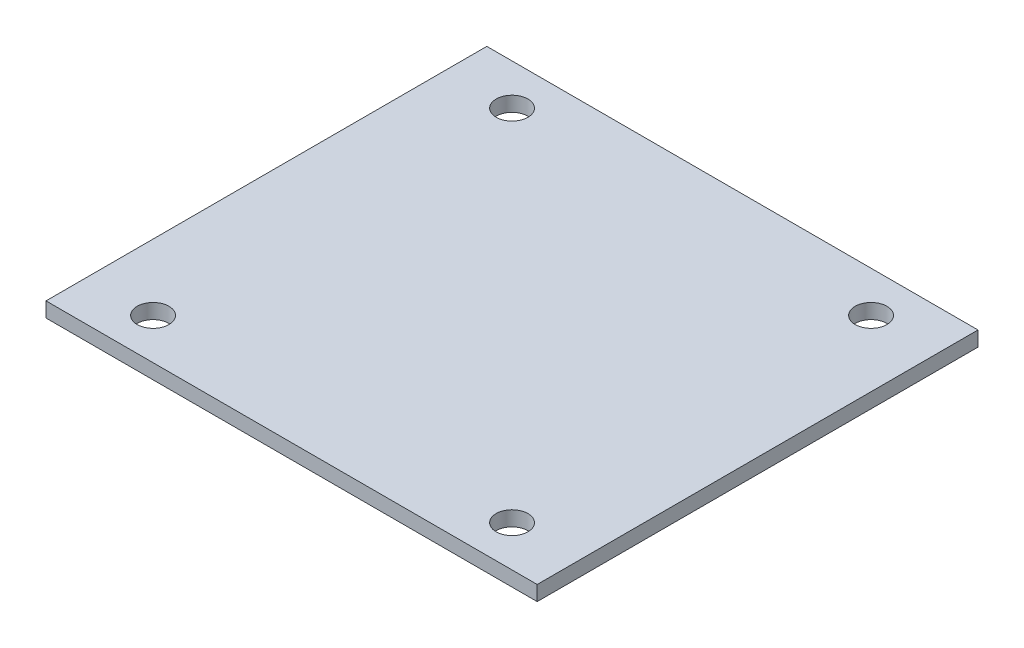
SolidWorks part; units mm, degrees
ref_plane "Front Plane" through (0, 0, 0) normal (0, 0, 1) x (1, 0, 0)
ref_plane "Top Plane" through (0, 0, 0) normal (0, 1, 0) x (1, 0, 0)
ref_plane "Right Plane" through (0, 0, 0) normal (1, 0, 0) x (0, 0, -1)
sketch "Sketch1" plane through (0, 0, 0) normal (0, 1, 0) x (1, 0, 0)
  line L0 (6.6675, 4.1275) -> (6.6675, 40.3275) construction
  line L1 (0, 44.45) -> (49.53, 44.45)
  line L2 (0, 44.45) -> (0, 0)
  line L3 (0, 0) -> (49.53, 0)
  line L4 (49.53, 44.45) -> (49.53, 0)
  line L5 (6.6675, 40.3275) -> (42.8675, 40.3275) construction
  line L6 (42.8675, 40.3275) -> (42.8675, 4.1275) construction
  line L7 (42.8675, 4.1275) -> (6.6675, 4.1275) construction
  circle A0 centre (6.6675, 4.1275) radius 1.6
  circle A1 centre (42.8675, 4.1275) radius 1.6
  circle A2 centre (42.8675, 40.3275) radius 1.6
  circle A3 centre (6.6675, 40.3275) radius 1.6
  dimension "D7" = 3.2
  dimension "D1" = 44.45
  dimension "D2" = 49.53
  dimension "D3" = 4.1275
  dimension "D4" = 6.6675
  dimension "D5" = 36.2
  dimension "D6" = 36.2
extrude "Boss-Extrude1" add sketch "Sketch1" along normal blind 1.5
